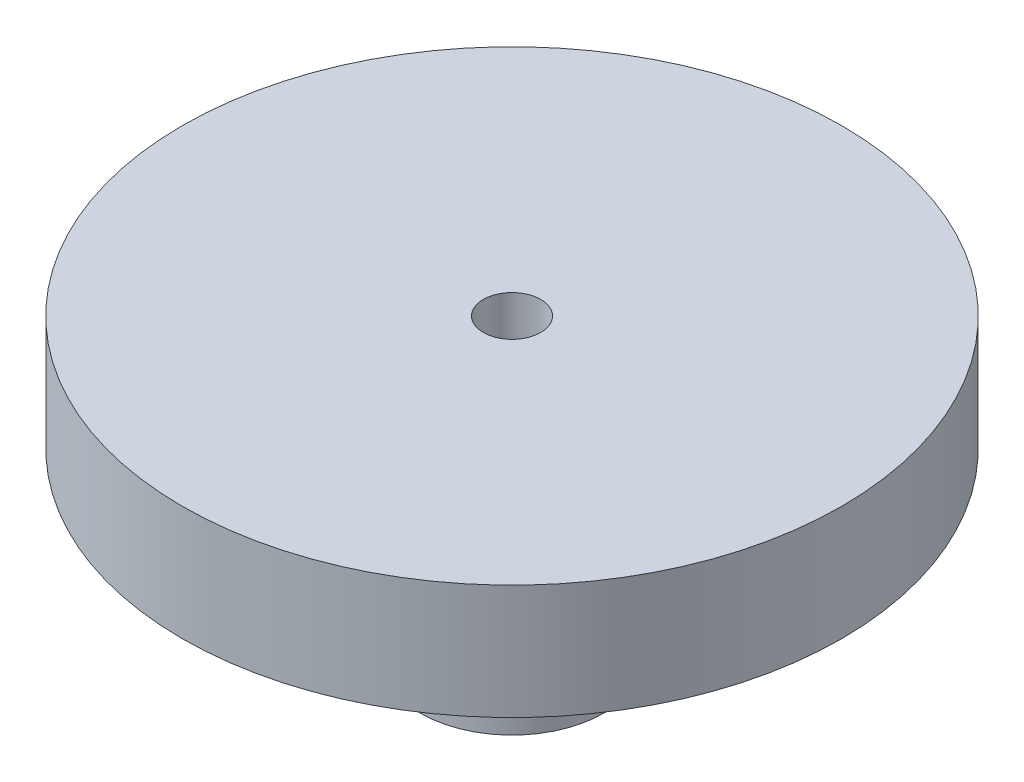
SolidWorks part; units mm, degrees
ref_plane "Front Plane" through (0, 0, 0) normal (0, 0, 1) x (1, 0, 0)
ref_plane "Top Plane" through (0, 0, 0) normal (0, 1, 0) x (1, 0, 0)
ref_plane "Right Plane" through (0, 0, 0) normal (1, 0, 0) x (0, 0, -1)
sketch "Sketch1" plane through (0, 0, 0) normal (0, 1, 0) x (1, 0, 0)
  circle A0 centre (0, 0) radius 2.5
  circle A1 centre (0, 0) radius 8
extrude "Boss-Extrude1" add sketch "Sketch1" along normal blind 16
sketch "Sketch2" plane through (0, 16, 0) normal (0, 1, 0) x (1, 0, 0)
  circle A0 centre (0, 0) radius 28.75
  circle A1 centre (0, 0) radius 2.5
extrude "Boss-Extrude2" add sketch "Sketch2" along normal blind 10
